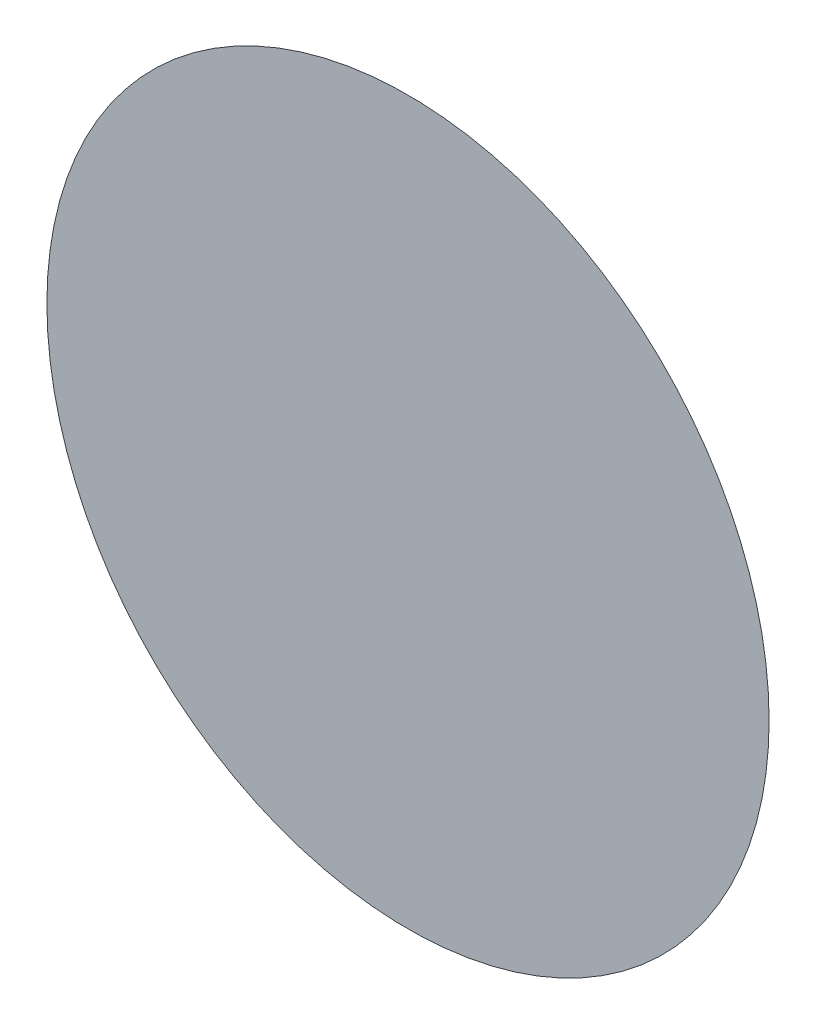
SolidWorks part; units mm, degrees
ref_plane "前视基准面" through (0, 0, 0) normal (0, 0, 1) x (1, 0, 0)
ref_plane "上视基准面" through (0, 0, 0) normal (0, 1, 0) x (1, 0, 0)
ref_plane "右视基准面" through (0, 0, 0) normal (1, 0, 0) x (0, 0, -1)
sketch "草图3" plane through (0, 0, 0) normal (0, 1, 0) x (1, 0, 0)
  line L0 (-100, 36.7331) -> (0, 36.7331)
  line L1 (0, 36.7331) -> (0, -33.2669)
  line L2 (0, -33.2669) -> (-200, -33.2669)
  line L3 (-200, -33.2669) -> (-100, 36.7331)
  point P2 (-290.5872, -33.2669)
  dimension "D1" = 100
  dimension "D2" = 200
  dimension "D3" = 70
revolve "旋转1" add sketch "草图3" angle 360 about L1
sketch "草图4" plane through (0, 0, -36.7331) normal (0, 0, -1) x (-1, 0, 0)
  line L0 (-46.25, 13.7477) -> (-46.25, -16.0467)
  line L1 (46.25, 13.7477) -> (46.25, -16.0467)
  arc A1 (-46.25, 13.7477) -> (46.25, 13.7477) centre (0, 0) cw
  arc A2 (-46.25, -16.0467) -> (46.25, -16.0467) centre (0, 0) ccw
  point P2 (46.25, 13.7477)
  dimension "D1" = 92.5
extrude "切除-拉伸1" cut sketch "草图4" against normal blind 34.3
